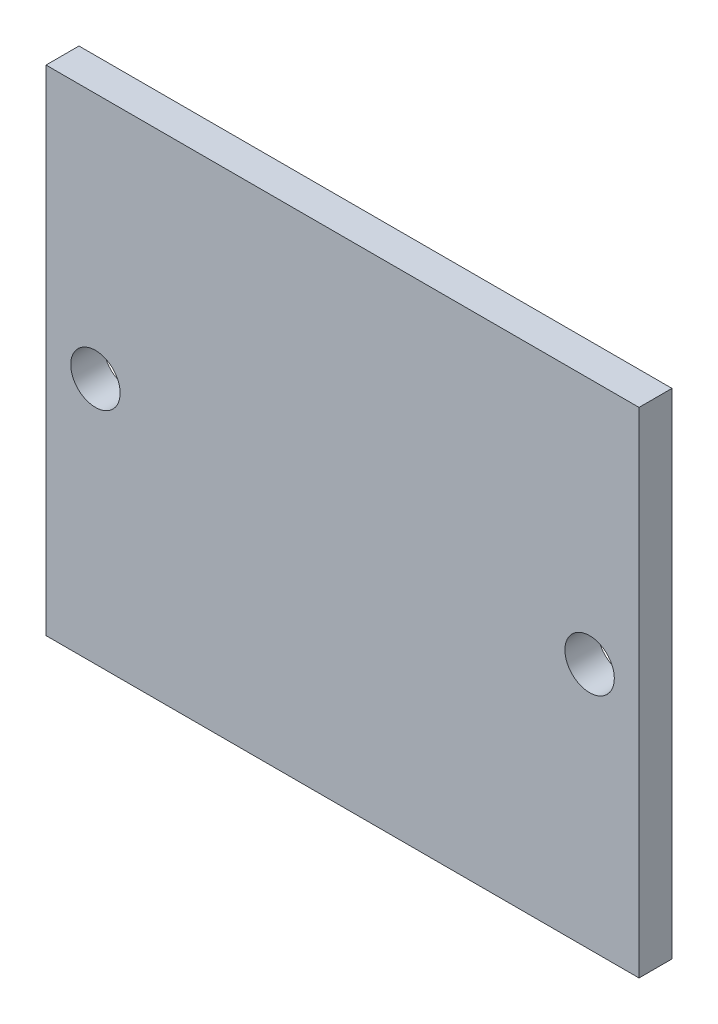
SolidWorks part; units mm, degrees
ref_plane "Front" through (0, 0, 0) normal (0, 0, 1) x (1, 0, 0)
ref_plane "Top" through (0, 0, 0) normal (0, 1, 0) x (1, 0, 0)
ref_plane "Right" through (0, 0, 0) normal (1, 0, 0) x (0, 0, -1)
sketch "草图1" plane through (0, 0, 0) normal (0, 0, 1) x (1, 0, 0)
  line L1 (-18, -15) -> (18, -15)
  line L2 (-18, -15) -> (-18, 15)
  line L3 (-18, 15) -> (18, 15)
  line L4 (18, -15) -> (18, 15)
  line L5 (-18, -15) -> (18, 15) construction
  line L6 (-18, 15) -> (18, -15) construction
  circle A1 centre (-15, 0) radius 1.5
  circle A2 centre (15, 0) radius 1.5
  point P0 (0, 0)
extrude "凸台-拉伸1" add sketch "草图1" along normal blind 2
